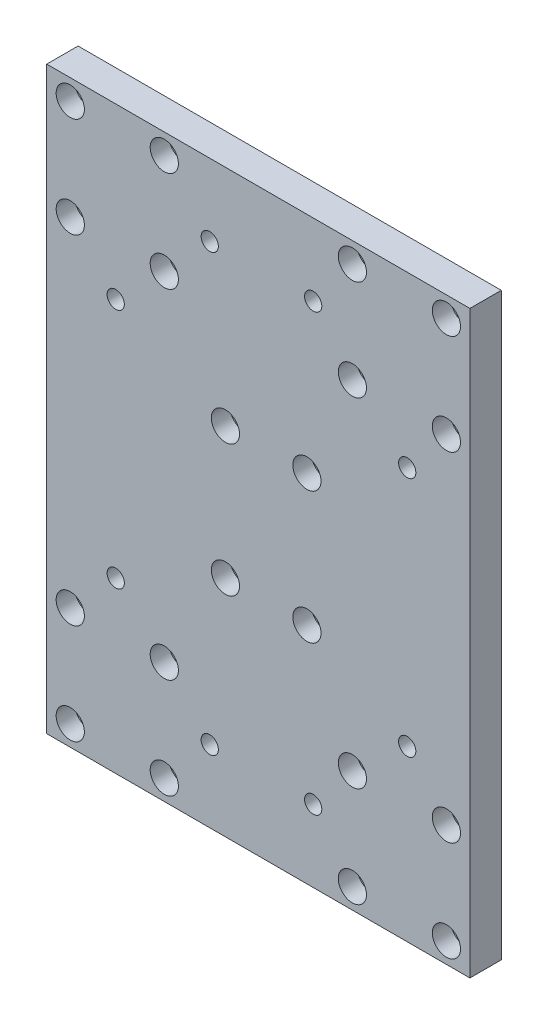
SolidWorks part; units mm, degrees
material "1.0037 (S235JR)"
ref_plane "Płaszczyzna przednia" through (0, 0, 0) normal (0, 0, 1) x (1, 0, 0)
ref_plane "Płaszczyzna górna" through (0, 0, 0) normal (0, 1, 0) x (1, 0, 0)
ref_plane "Płaszczyzna prawa" through (0, 0, 0) normal (1, 0, 0) x (0, 0, -1)
sketch "Szkic1" plane through (0, 0, 0) normal (0, 0, 1) x (1, 0, 0)
  line L1 (0, 0) -> (135, 0)
  line L2 (0, 0) -> (0, 185)
  line L3 (0, 185) -> (135, 185)
  line L4 (135, 0) -> (135, 185)
  dimension "D1" = 135
  dimension "D2" = 185
extrude "Dodanie-wyciągnięcie1" add sketch "Szkic1" along normal blind 10
sketch "Szkic2" plane through (0, 0, 10) normal (0, 0, 1) x (1, 0, 0)
  circle A0 centre (7.5, 178.5) radius 2.5 construction
  circle A1 centre (37.5, 178.5) radius 2.5 construction
  circle A2 centre (7.5, 146.5) radius 2.5 construction
  circle A3 centre (37.5, 146.5) radius 2.5 construction
  circle A4 centre (7.5, 38.5) radius 2.5 construction
  circle A5 centre (37.5, 38.5) radius 2.5 construction
  circle A6 centre (7.5, 6.5) radius 2.5 construction
  circle A7 centre (37.5, 6.5) radius 2.5 construction
  circle A8 centre (7.5, 178.5) radius 2.5
  circle A9 centre (37.5, 178.5) radius 2.5
  circle A10 centre (7.5, 146.5) radius 2.5
  circle A11 centre (37.5, 146.5) radius 2.5
  circle A12 centre (7.5, 38.5) radius 2.5
  circle A13 centre (37.5, 38.5) radius 2.5
  circle A14 centre (7.5, 6.5) radius 2.5
  circle A15 centre (37.5, 6.5) radius 2.5
hole_wizard "Pogłębienie walcowe pod M5 Wkręt do części metalowych z łbem sześciokątnym1" positions "Szkic4" profile "Szkic3" counterbore size "M5" standard "Ansi Metryczny" end condition through all
sketch "Szkic4" plane through (0, 0, 10) normal (0, 0, 1) x (1, 0, 0)
  line L0 (67.5, 185) -> (67.5, 0) construction
  line L1 (135, 185) -> (0, 185) construction
  line L2 (0, 0) -> (135, 0) construction
  point P0 (7.5, 178.5)
  point P1 (37.5, 178.5)
  point P4 (37.5, 146.5)
  point P7 (7.5, 146.5)
  point P10 (7.5, 38.5)
  point P13 (37.5, 38.5)
  point P16 (7.5, 6.5)
  point P19 (37.5, 6.5)
  point P33 (97.5, 6.5)
  point P34 (127.5, 6.5)
  point P35 (97.5, 38.5)
  point P36 (127.5, 38.5)
  point P37 (127.5, 146.5)
  point P38 (97.5, 146.5)
  point P39 (97.5, 178.5)
  point P40 (127.5, 178.5)
sketch "Szkic3" plane through (7.5, 178.5, 10) normal (1, 0, 0) x (0, -1, 0)
  line L0 (0, 0) -> (0, 10)
  line L1 (0, 10) -> (2.75, 10)
  line L3 (2.75, 10) -> (2.75, 6)
  line L4 (2.75, 6) -> (4.5, 6)
  line L5 (4.5, 6) -> (4.5, 0)
  line L7 (4.5, 0) -> (0, 0)
  line L11 (0, -6.35) -> (0, 107.95) construction
  dimension "Średnica otworu na wylot" = 5.5
  dimension "Głębokość otworu na wylot" = 10
  dimension "Średnica pogłębienia walcowego" = 9
  dimension "Głębokość pogłębienia walcowego" = 6
sketch "Szkic5" plane through (0, 0, 10) normal (0, 0, 1) x (1, 0, 0)
  line L0 (-30.7056, 92.5) -> (135, 92.5) construction
  line L2 (135, 0) -> (135, 185) construction
  circle A0 centre (22, 54) radius 2.75
  circle A1 centre (52, 23) radius 2.75
  circle A2 centre (85, 23) radius 2.75
  circle A3 centre (115, 54) radius 2.75
  circle A4 centre (115, 54) radius 2.75 construction
  circle A5 centre (85, 23) radius 2.75 construction
  circle A6 centre (52, 23) radius 2.75 construction
  circle A7 centre (22, 54) radius 2.75 construction
  circle A8 centre (52, 162) radius 2.75
  circle A9 centre (22, 131) radius 2.75
  circle A10 centre (115, 131) radius 2.75
  circle A11 centre (85, 162) radius 2.75
extrude "Wytnij-wyciągnięcie1" cut sketch "Szkic5" against normal through all
hole_wizard "Pogłębienie walcowe pod M5 Wkręt do części metalowych z łbem sześciokątnym2" positions "Szkic7" profile "Szkic6" counterbore size "M5" standard "Ansi Metric" end condition through all
sketch "Szkic7" plane through (0, 0, 10) normal (0, 0, 1) x (1, 0, 0)
  point P0 (83, 113.5)
  point P2 (57, 113.5)
  point P4 (57, 71.5)
  point P6 (83, 71.5)
sketch "Szkic6" plane through (83, 113.5, 10) normal (1, 0, 0) x (0, -1, 0)
  line L0 (0, 0) -> (0, 10)
  line L1 (0, 10) -> (2.75, 10)
  line L3 (2.75, 10) -> (2.75, 6)
  line L4 (2.75, 6) -> (4.5, 6)
  line L5 (4.5, 6) -> (4.5, 0)
  line L7 (4.5, 0) -> (0, 0)
  line L11 (0, -6.35) -> (0, 107.95) construction
  dimension "Średnica otworu na wylot" = 5.5
  dimension "Głębokość otworu na wylot" = 10
  dimension "Średnica pogłębienia walcowego" = 9
  dimension "Głębokość pogłębienia walcowego" = 6
